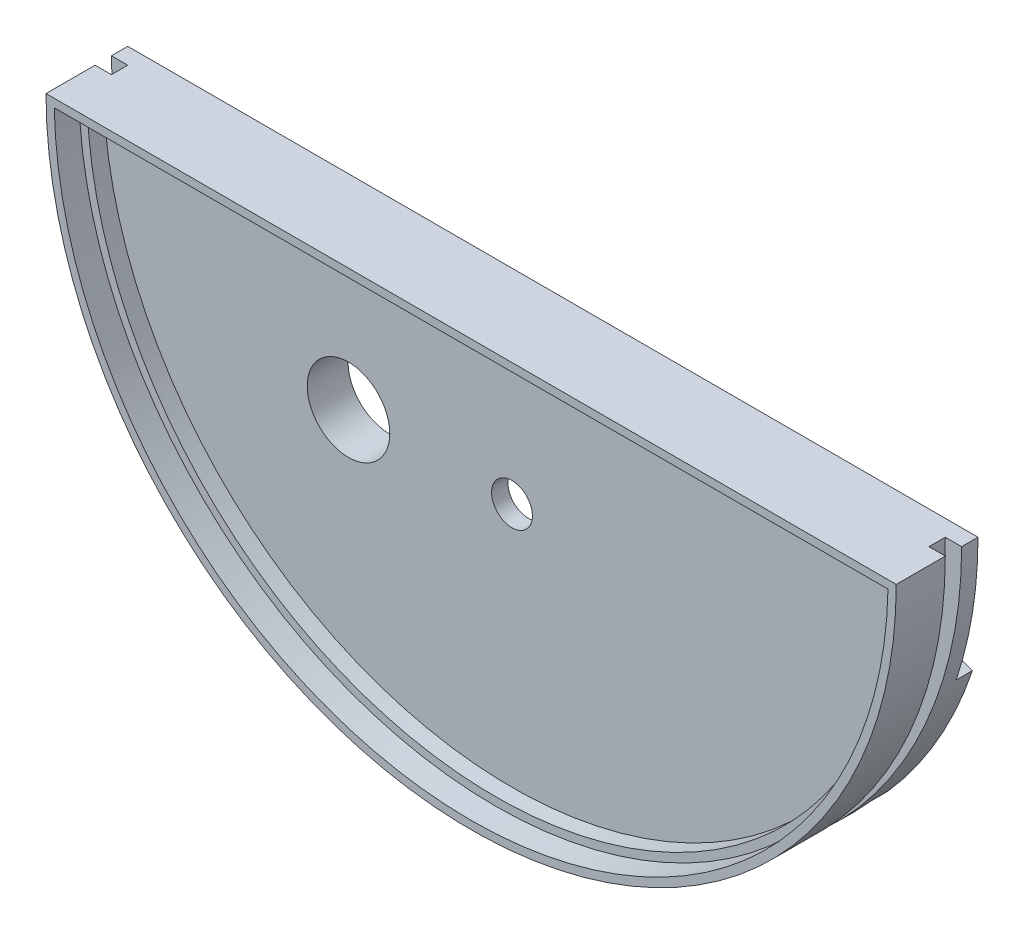
SolidWorks part; units mm, degrees
material "Acrylic (Medium-high impact)"
ref_plane "Front Plane" through (0, 0, 0) normal (0, 0, 1) x (1, 0, 0)
ref_plane "Top Plane" through (0, 0, 0) normal (0, 1, 0) x (1, 0, 0)
ref_plane "Right Plane" through (0, 0, 0) normal (1, 0, 0) x (0, 0, -1)
sketch "Sketch1" plane through (0, 0, 0) normal (0, 0, 1) x (1, 0, 0)
  line L0 (-52, 0) -> (52, 0)
  arc A0 (-52, 0) -> (52, 0) centre (0, 0) ccw
  circle A1 centre (-20, -20) radius 5.05
  dimension "D2" = 10.1
  dimension "D1" = 104
  dimension "D3" = 20
  dimension "D4" = 20
extrude "Boss-Extrude1" add sketch "Sketch1" against normal blind 5
sketch "Sketch2" plane through (0, 0, 0) normal (0, 0, 1) x (1, 0, 0)
  line L0 (49.96, -2) -> (-49.96, -2)
  line L1 (52, 0) -> (-52, 0)
  line L2 (52, 0) -> (-52, 0)
  arc A0 (-49.96, -2) -> (49.96, -2) centre (0, 0) ccw
  arc A1 (-52, 0) -> (52, 0) centre (0, 0) ccw
  arc A2 (-52, 0) -> (52, 0) centre (0, 0) ccw
  dimension "D1" = 0
  dimension "D2" = 2
extrude "Boss-Extrude2" add sketch "Sketch2" along normal blind 5
ref_plane "Plane1" through (0, 0, 4) normal (0, 0, 1) x (1, 0, 0)
ref_plane "Plane2" through (0, -52, 0) normal (0, -1, 0) x (-1, 0, 0)
sketch "Sketch5" plane through (0, 0, -5) normal (0, 0, -1) x (-1, 0, 0)
  line L0 (10, -48.9898) -> (10.4, -50.9494)
  line L1 (52, 0) -> (-52, 0)
  line L2 (52, 0) -> (-52, 0)
  line L3 (-10, -48.9898) -> (-10.4, -50.9494)
  line L4 (-37.4264, -33.1552) -> (-38.9235, -34.4814)
  line L5 (-47.4264, -15.8346) -> (-49.3235, -16.468)
  line L12 (47.4264, -15.8346) -> (49.3235, -16.468)
  line L13 (37.4264, -33.1552) -> (38.9235, -34.4814)
  line L14 (-47.4264, 15.8346) -> (-49.3235, 16.468) [skipped]
  line L15 (-37.4264, 33.1552) -> (-38.9235, 34.4814) [skipped]
  line L16 (-10, 48.9898) -> (-10.4, 50.9494) [skipped]
  line L17 (10, 48.9898) -> (10.4, 50.9494) [skipped]
  line L18 (37.4264, 33.1552) -> (38.9235, 34.4814) [skipped]
  line L19 (47.4264, 15.8346) -> (49.3235, 16.468) [skipped]
  arc A0 (-10, -48.9898) -> (10, -48.9898) centre (0, 0) ccw
  arc A1 (-52, 0) -> (52, 0) centre (0, 0) ccw
  arc A2 (-52, 0) -> (52, 0) centre (0, 0) ccw
  arc A3 (-47.4264, -15.8346) -> (-37.4264, -33.1552) centre (0, 0) ccw
  arc A7 (37.4264, -33.1552) -> (47.4264, -15.8346) centre (0, 0) ccw
  arc A8 (-37.4264, 33.1552) -> (-47.4264, 15.8346) centre (0, 0) ccw [skipped]
  arc A9 (10, 48.9898) -> (-10, 48.9898) centre (0, 0) ccw [skipped]
  arc A10 (47.4264, 15.8346) -> (37.4264, 33.1552) centre (0, 0) ccw [skipped]
  point P30 (0, 0)
  arc M22 (-52, 0) -> (52, 0) centre (0, 0) ccw
  dimension "D2" = 50
  dimension "D3" = 10
  dimension "D4" = 10
  dimension "D1" = 0
  dimension "D5" = 6
extrude "Boss-Extrude4" add sketch "Sketch5" along normal blind 2 contours A3 L5 L4 M22 | A0 L3 L0 M22 | A7 L13 L12 M22
sketch "Sketch6" plane through (0, 0, -5) normal (0, 0, -1) x (-1, 0, 0)
  line L0 (-52, 0) -> (52, 0) construction
  circle A0 centre (0, -20) radius 9.5
  circle A2 centre (20, -20) radius 5.05 construction
  circle A3 centre (20, -20) radius 5.05
  dimension "D1" = 19
  dimension "D2" = 20
extrude "Cut-Extrude1" cut sketch "Sketch6" against normal blind 3
sketch "Sketch7" plane through (0, 0, -2) normal (0, 0, -1) x (-1, 0, 0)
  circle A0 centre (0, -20) radius 2.5
  dimension "D1" = 5
extrude "Cut-Extrude2" cut sketch "Sketch7" against normal through all
sketch "Sketch8" plane through (0, 0, -5) normal (0, 0, -1) x (-1, 0, 0)
  circle A0 centre (-20, -20) radius 4
  circle A1 centre (20, -20) radius 5.05 construction
  circle A2 centre (20, -20) radius 5.05
  dimension "D2" = 8
  dimension "D1" = 20
extrude "Boss-Extrude5" add sketch "Sketch8" along normal blind 3 contours A0
sketch "Sketch9" plane through (0, 0, 5) normal (0, 0, 1) x (1, 0, 0)
  line L1 (52, 0) -> (-52, 0) construction
  line L4 (52, 0) -> (-52, 0)
  line L5 (50.9902, -1) -> (-50.9902, -1)
  arc A0 (-52, 0) -> (52, 0) centre (0, 0) ccw construction
  arc A1 (-52, 0) -> (52, 0) centre (0, 0) ccw
  arc A2 (-50.9902, -1) -> (50.9902, -1) centre (0, 0) ccw
  line M4 (-49.96, -2) -> (49.96, -2)
  arc M5 (49.96, -2) -> (-49.96, -2) centre (0, 0) cw
  dimension "D2" = 1
extrude "Cut-Extrude3" cut sketch "Sketch9" against normal blind 3 contours M4 M5 | L5 A2 M5 M4
sketch "Sketch10" plane through (0, 0, 0) normal (0, 1, 0) x (1, 0, 0)
  line L0 (52, 5) -> (-52, 5) construction
  line L1 (58.5963, 1) -> (50, 1)
  line L2 (58.5963, 1) -> (58.5963, 3)
  line L3 (58.5963, 3) -> (50, 3)
  line L4 (50, 1) -> (50, 3)
  line L5 (52, 5) -> (52, -5) construction
  dimension "D1" = 2
  dimension "D2" = 2
  dimension "D3" = 2
ref_axis "Axis1" through (0, 0, -7) along (0, 0, 1)
revolve "Cut-Revolve1" cut sketch "Sketch10" angle 180 about axis through (0, 0, -7) along (0, 0, 1)
sketch "Sketch11" plane through (0, 0, -5) normal (0, 0, -1) x (-1, 0, 0)
  circle A0 centre (20, -20) radius 8
  dimension "D1" = 16
ref_axis "Axis2" through (-20, -20, -5) along (0, 0, 1)
ref_plane "Plane3" through (0, -20, 0) normal (0, 1, 0) x (1, 0, 0)
sketch "Sketch12" plane through (0, -20, 0) normal (0, 1, 0) x (1, 0, 0)
  line L1 (-12, 5) -> (-28, 5)
  line L2 (-12, 5) -> (-28, 5)
  circle A0 centre (-12, 5) radius 2
  dimension "D2" = 4
  dimension "D1" = 0
revolve "Cut-Revolve2" cut sketch "Sketch12" angle 360 about axis through (-20, -20, -5) along (0, 0, 1)
